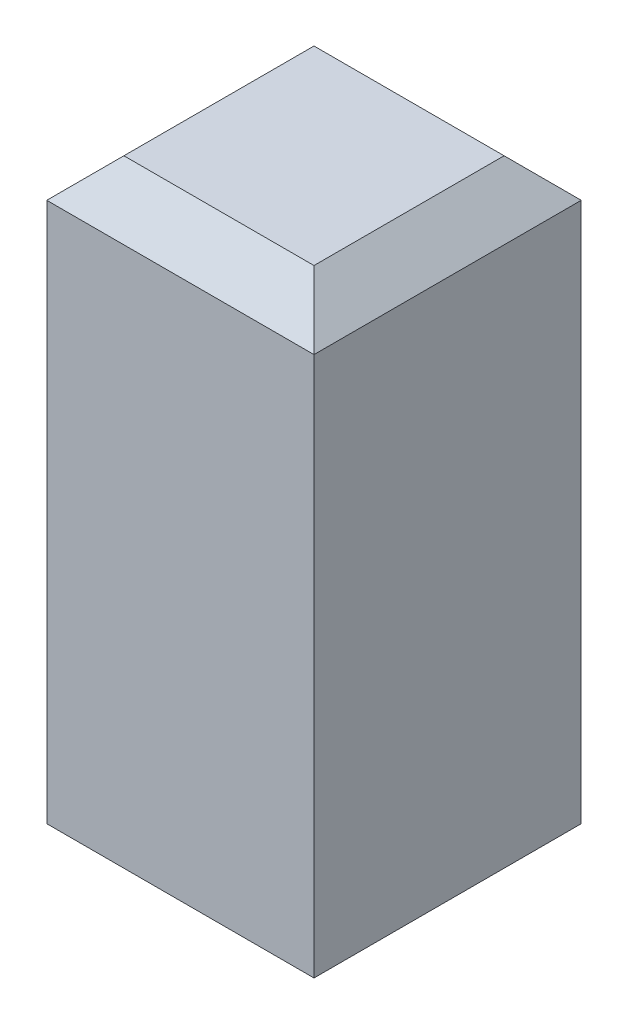
SolidWorks part; units mm, degrees
ref_plane "Front Plane" through (0, 0, 0) normal (0, 0, 1) x (1, 0, 0)
ref_plane "Top Plane" through (0, 0, 0) normal (0, 1, 0) x (1, 0, 0)
ref_plane "Right Plane" through (0, 0, 0) normal (1, 0, 0) x (0, 0, -1)
sketch "Sketch1" plane through (0, 0, 0) normal (0, 1, 0) x (1, 0, 0)
  line L5 (0, 0) -> (4.4003, 0)
  line L6 (0, 0) -> (0, 4.4003)
  line L7 (0, 4.4003) -> (4.4003, 4.4003)
  line L8 (4.4003, 0) -> (4.4003, 4.4003)
  dimension "D1" = 6.223
extrude "Boss-Extrude1" add sketch "Sketch1" along normal blind 10.16
chamfer "Chamfer1" distance 0.635 angle 45 8 edges at (2.2002, 0, 0) (4.4003, 0, -2.2002) (2.2002, 0, -4.4003) (0, 0, -2.2002) (2.2002, 10.16, -4.4003) (4.4003, 10.16, -2.2002) (2.2002, 10.16, 0) (0, 10.16, -2.2002)
